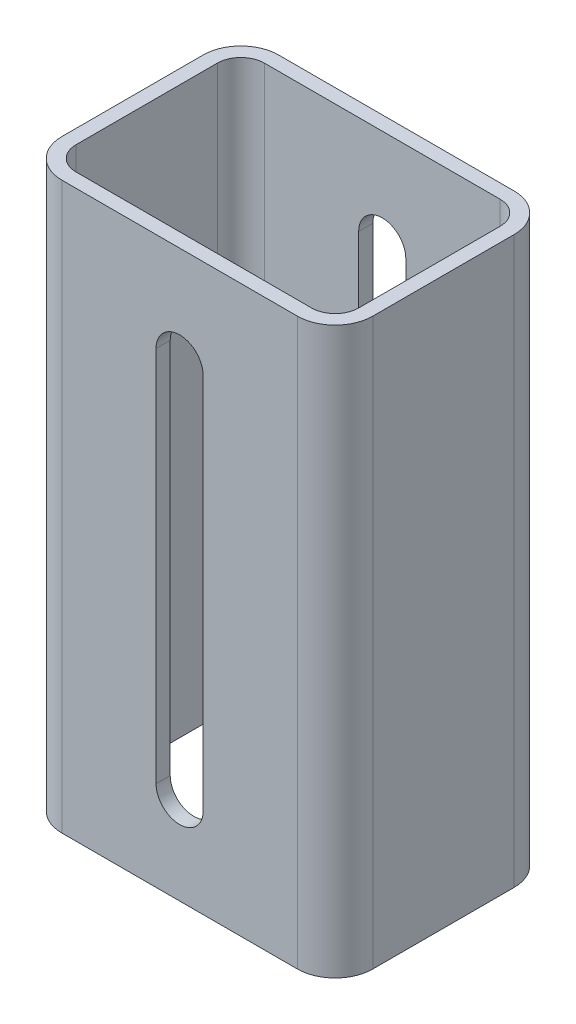
SolidWorks part; units mm, degrees
ref_plane "Front Plane" through (0, 0, 0) normal (0, 0, 1) x (1, 0, 0)
ref_plane "Top Plane" through (0, 0, 0) normal (0, 1, 0) x (1, 0, 0)
ref_plane "Right Plane" through (0, 0, 0) normal (1, 0, 0) x (0, 0, -1)
sketch "Sketch1" plane through (0, 0, 0) normal (0, 1, 0) x (1, 0, 0)
  line L1 (-25, 20) -> (25, 20)
  line L2 (-30, 15) -> (-30, -15)
  line L3 (-25, -20) -> (25, -20)
  line L4 (30, 15) -> (30, -15)
  line L5 (-30, 20) -> (30, -20) construction
  line L6 (-30, -20) -> (30, 20) construction
  arc A0 (-30, 15) -> (-25, 20) centre (-25, 15) cw
  arc A1 (30, 15) -> (25, 20) centre (25, 15) ccw
  arc A2 (-25, -20) -> (-30, -15) centre (-25, -15) cw
  arc A3 (25, -20) -> (30, -15) centre (25, -15) ccw
  point P0 (0, 0)
  dimension "D3" = 5
  dimension "D4" = 5
  dimension "D5" = 5
  dimension "D6" = 5
  dimension "D1" = 60
  dimension "D2" = 40
extrude "Extrude-Thin1" add sketch "Sketch1" along normal mid plane 120 thin thin type one direction wall 3
sketch "Sketch3" plane through (0, 0, -23) normal (0, 0, -1) x (-1, 0, 0)
  line L0 (0, -40.9376) -> (0, 39.0624) construction
  line L3 (-5, -40.9376) -> (-5, 39.0624)
  line L6 (5, -40.9376) -> (5, 39.0624)
  line L7 (25, 60) -> (25, -60) construction
  line L8 (-25, 60) -> (-25, -60) construction
  arc A4 (-5, -40.9376) -> (5, -40.9376) centre (0, -40.9376) ccw
  arc A5 (5, 39.0624) -> (-5, 39.0624) centre (0, 39.0624) ccw
  point P3 (0, -0.9376)
  dimension "D1" = 10
  dimension "D2" = 90
extrude "Cut-Extrude1" cut sketch "Sketch3" against normal through all both and the other way through all
